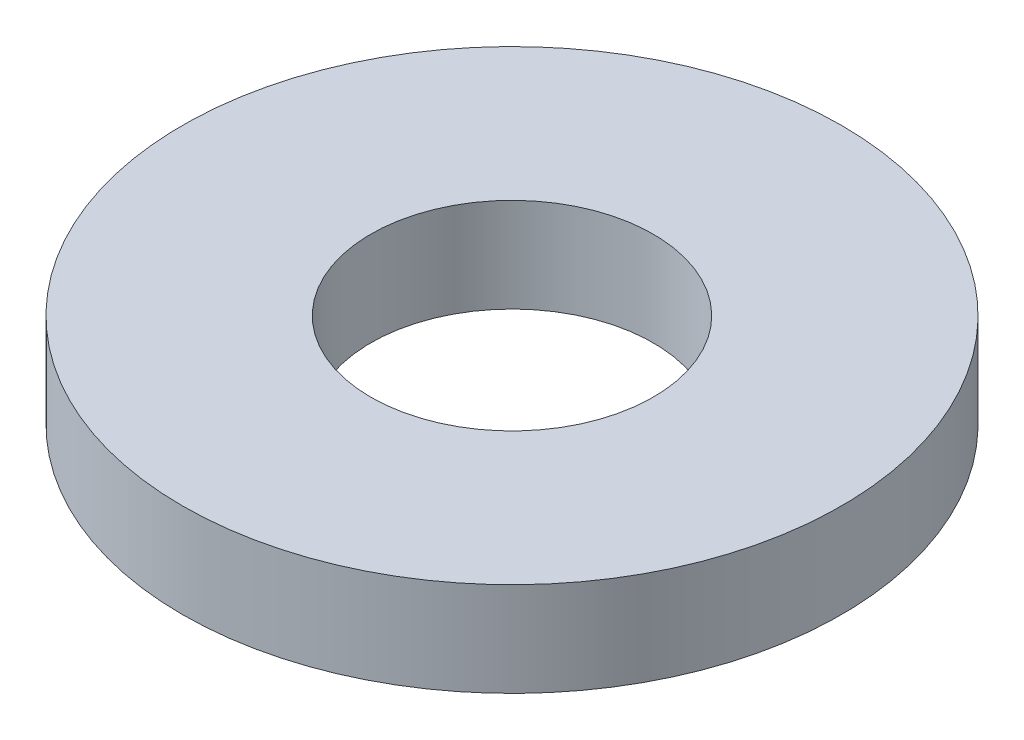
SolidWorks part; units mm, degrees
material "AISI 304"
ref_plane "前视基准面" through (0, 0, 0) normal (0, 0, 1) x (1, 0, 0)
ref_plane "上视基准面" through (0, 0, 0) normal (0, 1, 0) x (1, 0, 0)
ref_plane "右视基准面" through (0, 0, 0) normal (1, 0, 0) x (0, 0, -1)
other "Configuration Table"
sketch "草图1" plane through (0, 0, 0) normal (0, 1, 0) x (1, 0, 0)
  circle A0 centre (0, 0) radius 3.5
  circle A1 centre (0, 0) radius 1.5
  dimension "D1" = 3
  dimension "D2" = 7
extrude "凸台-拉伸1" add sketch "草图1" along normal blind 1
